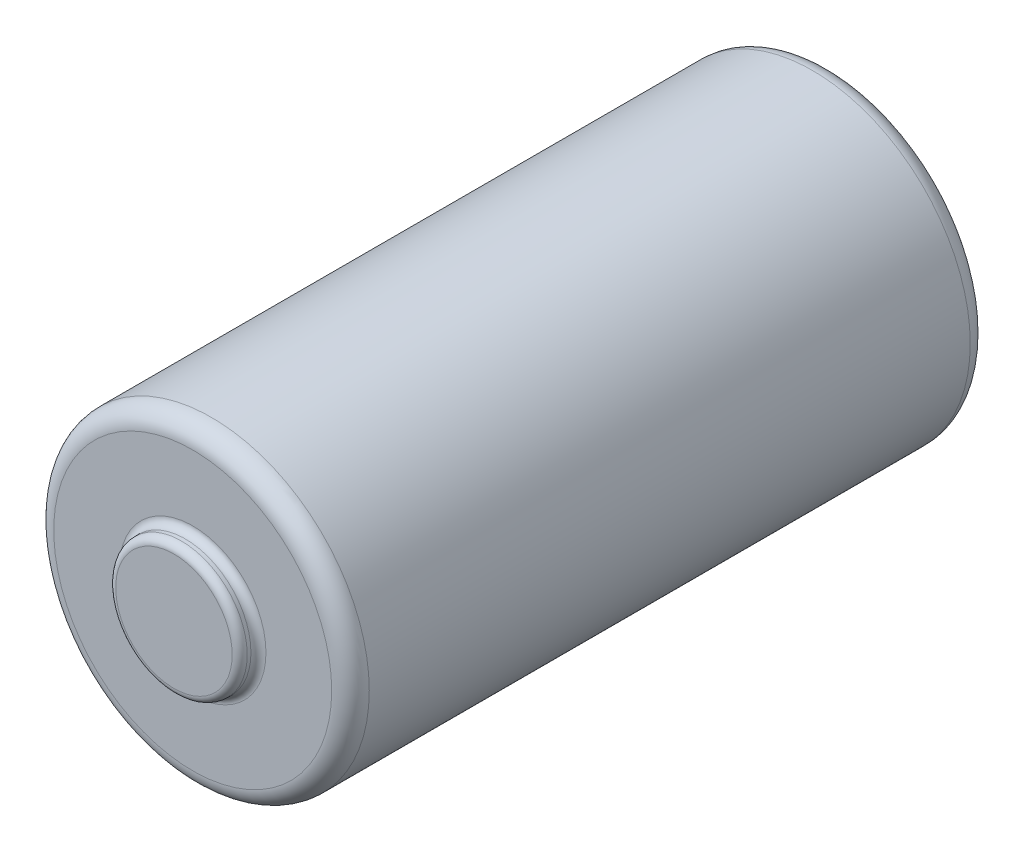
SolidWorks part; units mm, degrees
ref_plane "Front Plane" through (0, 0, 0) normal (0, 0, 1) x (1, 0, 0)
ref_plane "Top Plane" through (0, 0, 0) normal (0, 1, 0) x (1, 0, 0)
ref_plane "Right Plane" through (0, 0, 0) normal (1, 0, 0) x (0, 0, -1)
sketch "Sketch1" plane through (0, 0, 0) normal (0, 0, 1) x (1, 0, 0)
  circle A0 centre (0, 0) radius 8.4
  dimension "D1" = 16.8
extrude "Boss-Extrude1" add sketch "Sketch1" along normal blind 34
sketch "Sketch2" plane through (0, 0, 34) normal (0, 0, 1) x (1, 0, 0)
  circle A0 centre (0, 0) radius 3.5
  dimension "D1" = 7
extrude "Boss-Extrude2" add sketch "Sketch2" along normal blind 1
fillet "Fillet1" radius 1 2 edges at (8.4, 0, 0) (8.4, 0, 34)
fillet "Fillet2" radius 0.4 2 edges at (3.5, 0, 35) (3.5, 0, 34)
